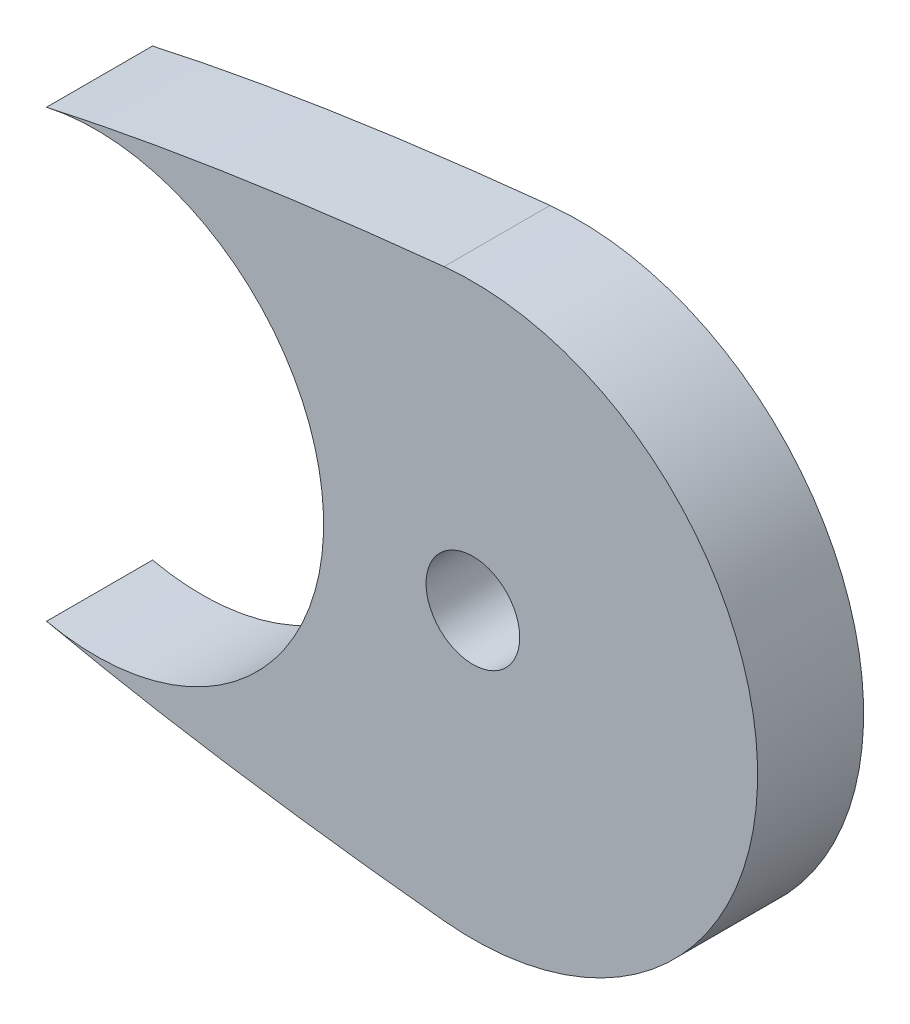
SolidWorks part; units mm, degrees
ref_plane "Front Plane" through (0, 0, 0) normal (0, 0, 1) x (1, 0, 0)
ref_plane "Top Plane" through (0, 0, 0) normal (0, 1, 0) x (1, 0, 0)
ref_plane "Right Plane" through (0, 0, 0) normal (1, 0, 0) x (0, 0, -1)
curve "Curve2"
  spline degree 3 poles (300, 0.378, 0) (299.8459, 0.3996, 0) (299.2303, 0.4859, 0) (297.8489, 0.6785, 0) (295.556, 0.9968, 0) (292.3657, 1.4334, 0) (288.2979, 1.9834, 0) (283.3772, 2.6357, 0) (277.6343, 3.3815, 0) (271.1045, 4.209, 0) (263.8281, 5.1072, 0) (255.8498, 6.0628, 0) (247.219, 7.0642, 0) (237.9888, 8.0979, 0) (228.216, 9.1511, 0) (217.9611, 10.2107, 0) (207.2872, 11.2632, 0) (196.2601, 12.2937, 0) (184.9478, 13.2887, 0) (173.4201, 14.2316, 0) (161.7479, 15.107, 0) (150.0032, 15.8986, 0) (138.2584, 16.5898, 0) (126.5858, 17.1634, 0) (115.0575, 17.6038, 0) (103.7442, 17.8968, 0) (92.7158, 18.028, 0) (82.0402, 17.9871, 0) (71.7831, 17.7661, 0) (62.0077, 17.3595, 0) (52.7741, 16.7661, 0) (44.1391, 15.9878, 0) (36.1555, 15.0306, 0) (28.872, 13.9026, 0) (22.3327, 12.6157, 0) (16.576, 11.1845, 0) (11.6345, 9.6228, 0) (7.5334, 7.9452, 0) (4.2857, 6.163, 0) (1.8965, 4.2728, 0) (0.3663, 2.2288, 0) (-0.1707, 0, 0) (0.3663, -2.2288, 0) (1.8965, -4.2728, 0) (4.2857, -6.163, 0) (7.5334, -7.9452, 0) (11.6345, -9.6228, 0) (16.576, -11.1845, 0) (22.3327, -12.6157, 0) (28.872, -13.9026, 0) (36.1555, -15.0306, 0) (44.1391, -15.9878, 0) (52.7741, -16.7661, 0) (62.0077, -17.3595, 0) (71.7831, -17.7661, 0) (82.0402, -17.9871, 0) (92.7158, -18.028, 0) (103.7442, -17.8968, 0) (115.0575, -17.6038, 0) (126.5858, -17.1634, 0) (138.2584, -16.5898, 0) (150.0032, -15.8986, 0) (161.7479, -15.107, 0) (173.4201, -14.2316, 0) (184.9478, -13.2887, 0) (196.2601, -12.2937, 0) (207.2872, -11.2632, 0) (217.9611, -10.2107, 0) (228.216, -9.1511, 0) (237.9888, -8.0979, 0) (247.219, -7.0642, 0) (255.8498, -6.0628, 0) (263.8281, -5.1072, 0) (271.1045, -4.209, 0) (277.6343, -3.3815, 0) (283.3772, -2.6357, 0) (288.2979, -1.9834, 0) (292.3657, -1.4334, 0) (295.556, -0.9968, 0) (297.8489, -0.6785, 0) (299.2303, -0.4859, 0) (299.8459, -0.3996, 0) (300, -0.378, 0) knots 0 0 0 0 0.000763 0.003048 0.006841 0.012116 0.018841 0.026973 0.03646 0.047243 0.059254 0.072417 0.086651 0.101866 0.117969 0.134858 0.152428 0.170572 0.189175 0.208122 0.227297 0.24658 0.265853 0.284997 0.303895 0.322433 0.340499 0.357984 0.374788 0.390812 0.405965 0.420162 0.433328 0.445394 0.456301 0.466004 0.474472 0.481696 0.487704 0.492583 0.496544 0.5 0.503456 0.507417 0.512296 0.518304 0.525528 0.533996 0.543699 0.554606 0.566672 0.579838 0.594035 0.609188 0.625212 0.642016 0.659501 0.677567 0.696105 0.715003 0.734147 0.75342 0.772703 0.791878 0.810825 0.829428 0.847572 0.865142 0.882031 0.898134 0.913349 0.927583 0.940746 0.952757 0.96354 0.973027 0.981159 0.987884 0.993159 0.996952 0.999237 1 1 1 1
sketch "Sketch2" plane through (0, 0, 0) normal (0, 0, 1) x (1, 0, 0)
  line L0 (0, 0) -> (300.3287, 0) construction
  line L9 (300, 0.378) -> (300, -0.378)
  line L17 (90, 18.0052) -> (90, -18.0052)
  line L20 (25.2817, 12.903) -> (25.2817, -12.903)
  line L21 (46.6322, 16.1183) -> (46.6322, -16.1183)
  line L22 (68.2099, 17.5933) -> (68.2099, -17.5933)
  line L23 (131.5031, 16.8963) -> (131.5031, -16.8963)
  line L24 (173.2123, 14.1909) -> (173.2123, -14.1909)
  line L25 (215.2898, -10.4186) -> (215.2898, 10.4186)
  line L26 (257.3103, -5.8439) -> (257.3103, 5.8439)
  arc A0 (300, -0.378) -> (300, 0.378) centre (299.947, 0) ccw
  arc A3 (45, 16.0354) -> (45, -16.0354) centre (46.6322, 0) ccw
  arc A5 (67.5, -17.5789) -> (67.5, 17.5789) centre (68.2099, 0) cw
  arc A6 (22.5, 12.5996) -> (22.5, -12.5996) centre (25.2817, 0) ccw
  arc A7 (258, -5.8031) -> (258, 5.8031) centre (257.3103, 0) cw
  arc A8 (216.3287, -10.3667) -> (216.3287, 10.3667) centre (215.2898, 0) cw
  arc A9 (174.3287, -14.147) -> (174.3287, 14.147) centre (173.2123, 0) cw
  arc A11 (132.3287, -16.8761) -> (132.3287, 16.8761) centre (131.5031, 0) cw
  arc A12 (90, -18.0052) -> (90, 18.0052) centre (89.9987, 0) cw
  arc A13 (22.5, 12.5996) -> (22.5, -12.5996) centre (25.2817, 0) cw
  arc A14 (45, 16.0354) -> (45, -16.0354) centre (46.6322, 0) cw
  arc A15 (67.5, 17.5789) -> (67.5, -17.5789) centre (68.2099, 0) cw
  arc A16 (90, -18.0052) -> (90, 18.0052) centre (90, 0) ccw
  arc A17 (132.3287, 16.8761) -> (132.3287, -16.8761) centre (131.5031, 0) cw
  arc A18 (174.3287, 14.147) -> (174.3287, -14.147) centre (173.2123, 0) cw
  arc A19 (216.3287, 10.3667) -> (216.3287, -10.3667) centre (215.2898, 0) cw
  arc A20 (257.9987, 5.8032) -> (257.9987, -5.8032) centre (257.309, 0) cw
  circle A21 centre (25.2817, 0) radius 12.903
  circle A22 centre (257.3103, 0) radius 5.8439
  circle A23 centre (25.2817, 0) radius 2.65
  circle A24 centre (8, 0) radius 2.65
  circle A25 centre (46.6322, 0) radius 2.65
  spline S0 degree 3 poles (1085.0864, 3916.8712) (453.7719, -29.1916) (376.7513, -10.3218) (297.8489, 0.6785) (295.556, 0.9968) (292.3657, 1.4334) (288.2979, 1.9834) (283.3772, 2.6357) (277.6343, 3.3815) (271.1045, 4.209) (263.8281, 5.1072) (255.8498, 6.0628) (247.219, 7.0642) (237.9888, 8.0979) (228.216, 9.1511) (217.9611, 10.2107) (207.2872, 11.2632) (196.2601, 12.2937) (184.9478, 13.2887) (173.4201, 14.2316) (161.7479, 15.107) (150.0032, 15.8986) (138.2584, 16.5898) (126.5858, 17.1634) (115.0575, 17.6038) (103.7442, 17.8968) (92.7158, 18.028) (82.0402, 17.9871) (71.7831, 17.7661) (62.0077, 17.3595) (52.7741, 16.7661) (44.1391, 15.9878) (36.1555, 15.0306) (28.872, 13.9026) (22.3327, 12.6157) (16.576, 11.1845) (11.6345, 9.6228) (7.5334, 7.9452) (4.2857, 6.163) (1.8965, 4.2728) (0.3663, 2.2288) (-0.1707, 0) (0.3663, -2.2288) (1.8965, -4.2728) (4.2857, -6.163) (7.5334, -7.9452) (11.6345, -9.6228) (16.576, -11.1845) (22.3327, -12.6157) (28.872, -13.9026) (36.1555, -15.0306) (44.1391, -15.9878) (52.7741, -16.7661) (62.0077, -17.3595) (71.7831, -17.7661) (82.0402, -17.9871) (92.7158, -18.028) (103.7442, -17.8968) (115.0575, -17.6038) (126.5858, -17.1634) (138.2584, -16.5898) (150.0032, -15.8986) (161.7479, -15.107) (173.4201, -14.2316) (184.9478, -13.2887) (196.2601, -12.2937) (207.2872, -11.2632) (217.9611, -10.2107) (228.216, -9.1511) (237.9888, -8.0979) (247.219, -7.0642) (255.8498, -6.0628) (263.8281, -5.1072) (271.1045, -4.209) (277.6343, -3.3815) (283.3772, -2.6357) (288.2979, -1.9834) (292.3657, -1.4334) (295.556, -0.9968) (297.8489, -0.6785) (376.7507, 10.3217) (453.7706, 29.1913) (1085.0706, -3916.7726) knots -0.383871 -0.383871 -0.383871 -0.383871 0.000763 0.003048 0.006841 0.012116 0.018841 0.026973 0.03646 0.047243 0.059254 0.072417 0.086651 0.101866 0.117969 0.134858 0.152428 0.170572 0.189175 0.208122 0.227297 0.24658 0.265853 0.284997 0.303895 0.322433 0.340499 0.357984 0.374788 0.390812 0.405965 0.420162 0.433328 0.445394 0.456301 0.466004 0.474472 0.481696 0.487704 0.492583 0.496544 0.5 0.503456 0.507417 0.512296 0.518304 0.525528 0.533996 0.543699 0.554606 0.566672 0.579838 0.594035 0.609188 0.625212 0.642016 0.659501 0.677567 0.696105 0.715003 0.734147 0.75342 0.772703 0.791878 0.810825 0.829428 0.847572 0.865142 0.882031 0.898134 0.913349 0.927583 0.940746 0.952757 0.96354 0.973027 0.981159 0.987884 0.993159 0.996952 0.999237 1.383868 1.383868 1.383868 1.383868 only from (300, 0.378) to (300, -0.378) construction
  spline S1 degree 3 poles (300, 0.378) (299.8459, 0.3996) (299.2303, 0.4859) (297.8489, 0.6785) (295.556, 0.9968) (292.3657, 1.4334) (288.2979, 1.9834) (283.3772, 2.6357) (277.6343, 3.3815) (271.1045, 4.209) (263.8281, 5.1072) (255.8498, 6.0628) (247.219, 7.0642) (237.9888, 8.0979) (228.216, 9.1511) (217.9611, 10.2107) (207.2872, 11.2632) (196.2601, 12.2937) (184.9478, 13.2887) (173.4201, 14.2316) (161.7479, 15.107) (150.0032, 15.8986) (138.2584, 16.5898) (126.5858, 17.1634) (115.0575, 17.6038) (103.7442, 17.8968) (92.7158, 18.028) (82.0402, 17.9871) (71.7831, 17.7661) (62.0077, 17.3595) (52.7741, 16.7661) (44.1391, 15.9878) (36.1555, 15.0306) (28.872, 13.9026) (22.3327, 12.6157) (16.576, 11.1845) (11.6345, 9.6228) (7.5334, 7.9452) (4.2857, 6.163) (1.8965, 4.2728) (0.3663, 2.2288) (-0.1707, 0) (0.3663, -2.2288) (1.8965, -4.2728) (4.2857, -6.163) (7.5334, -7.9452) (11.6345, -9.6228) (16.576, -11.1845) (22.3327, -12.6157) (28.872, -13.9026) (36.1555, -15.0306) (44.1391, -15.9878) (52.7741, -16.7661) (62.0077, -17.3595) (71.7831, -17.7661) (82.0402, -17.9871) (92.7158, -18.028) (103.7442, -17.8968) (115.0575, -17.6038) (126.5858, -17.1634) (138.2584, -16.5898) (150.0032, -15.8986) (161.7479, -15.107) (173.4201, -14.2316) (184.9478, -13.2887) (196.2601, -12.2937) (207.2872, -11.2632) (217.9611, -10.2107) (228.216, -9.1511) (237.9888, -8.0979) (247.219, -7.0642) (255.8498, -6.0628) (263.8281, -5.1072) (271.1045, -4.209) (277.6343, -3.3815) (283.3772, -2.6357) (288.2979, -1.9834) (292.3657, -1.4334) (295.556, -0.9968) (297.8489, -0.6785) (299.2303, -0.4859) (299.8459, -0.3996) (300, -0.378) knots 0 0 0 0 0.000763 0.003048 0.006841 0.012116 0.018841 0.026973 0.03646 0.047243 0.059254 0.072417 0.086651 0.101866 0.117969 0.134858 0.152428 0.170572 0.189175 0.208122 0.227297 0.24658 0.265853 0.284997 0.303895 0.322433 0.340499 0.357984 0.374788 0.390812 0.405965 0.420162 0.433328 0.445394 0.456301 0.466004 0.474472 0.481696 0.487704 0.492583 0.496544 0.5 0.503456 0.507417 0.512296 0.518304 0.525528 0.533996 0.543699 0.554606 0.566672 0.579838 0.594035 0.609188 0.625212 0.642016 0.659501 0.677567 0.696105 0.715003 0.734147 0.75342 0.772703 0.791878 0.810825 0.829428 0.847572 0.865142 0.882031 0.898134 0.913349 0.927583 0.940746 0.952757 0.96354 0.973027 0.981159 0.987884 0.993159 0.996952 0.999237 1 1 1 1
  point P47 (215.2898, 0)
  point P58 (257.3103, 0)
  point P61 (12.3787, 0)
  point P62 (62.7505, 0)
  dimension "D11" = 5.3
  dimension "D14" = 5.3
  dimension "D12" = 5.3
  dimension "D1" = 300.3287
  dimension "D2" = 89.9987
  dimension "D3" = 68.2099
  dimension "D4" = 46.6322
  dimension "D5" = 25.2817
  dimension "D6" = 168.8256
  dimension "D7" = 127.1164
  dimension "D8" = 85.0389
  dimension "D9" = 43.0184
  dimension "D10" = 50.3718
  dimension "D13" = 8
extrude "Boss-Extrude2" add sketch "Sketch2" along normal blind 6 contours A3 S1 A13 | A13 S1 A3 | A13 L0 L21 A14 A3 | L0 A21 A3 A14 L21 | L21 L0 A5 A14 | L0 L21 A14 A5 | A5 L0 A14 | L0 A5 A14
